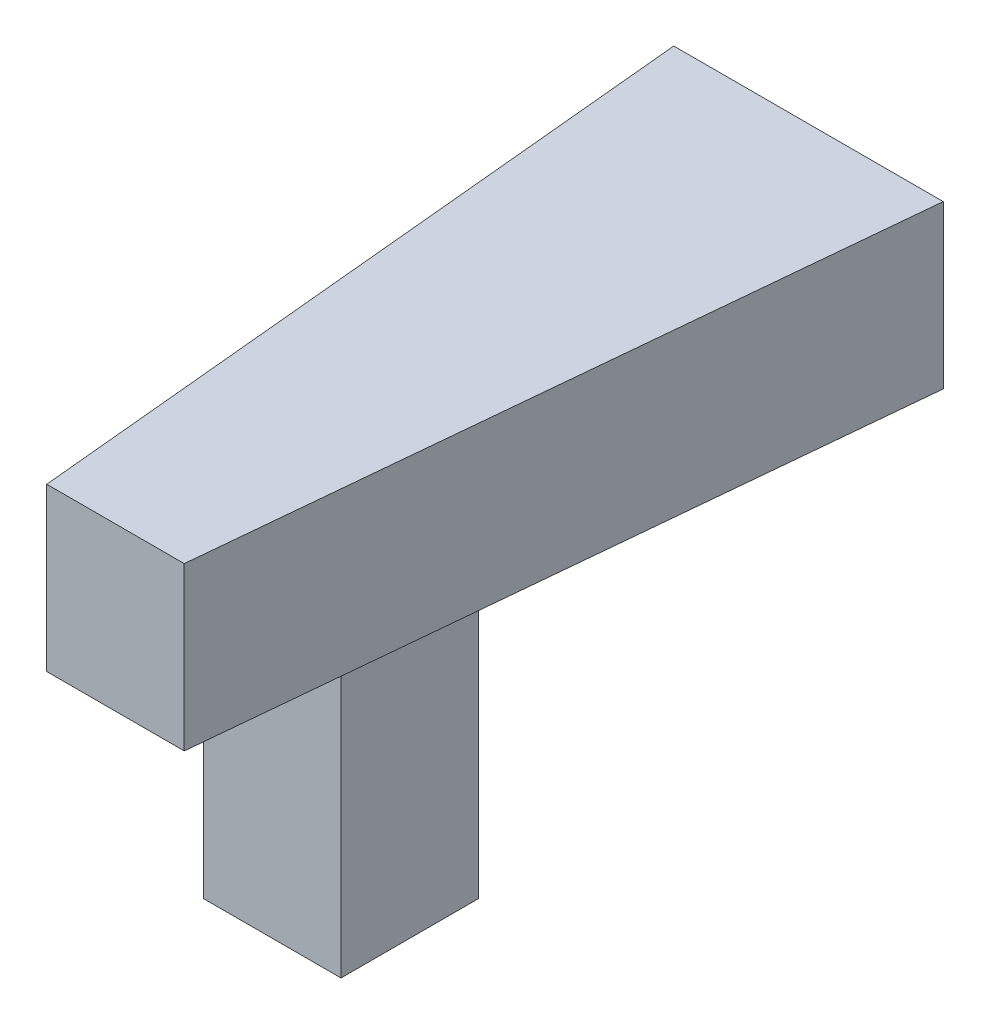
SolidWorks part; units mm, degrees
ref_plane "Front Plane" through (0, 0, 0) normal (0, 0, 1) x (1, 0, 0)
ref_plane "Top Plane" through (0, 0, 0) normal (0, 1, 0) x (1, 0, 0)
ref_plane "Right Plane" through (0, 0, 0) normal (1, 0, 0) x (0, 0, -1)
sketch "Sketch1" plane through (0, 0, 0) normal (0, 1, 0) x (1, 0, 0)
  line L0 (-25, -10) -> (25, -10)
  line L5 (-49, 242) -> (49, 242)
  line L6 (-49, 242) -> (-25, -10)
  line L7 (49, 242) -> (25, -10)
  line L8 (0, -10) -> (0, 0) construction
  point P3 (0, 0)
  point P9 (0, 242)
  dimension "D1" = 50
  dimension "D2" = 98
  dimension "D3" = 252
  dimension "D4" = 10
extrude "Boss-Extrude1" add sketch "Sketch1" along normal blind 59
sketch "Sketch3" plane through (0, 0, 0) normal (0, 1, 0) x (1, 0, 0)
  line L1 (-25, 97) -> (25, 97)
  line L2 (-25, 97) -> (-25, 47)
  line L3 (-25, 47) -> (25, 47)
  line L4 (25, 97) -> (25, 47)
  line L5 (-25, 97) -> (25, 47) construction
  line L6 (-25, 47) -> (25, 97) construction
  line L7 (-25, -10) -> (25, -10) construction
  point P0 (0, 72)
  point P5 (0, 0)
  point P8 (0, -10)
  dimension "D1" = 50
  dimension "D2" = 50
  dimension "D3" = 72
extrude "Boss-Extrude2" add sketch "Sketch3" against normal blind 100
